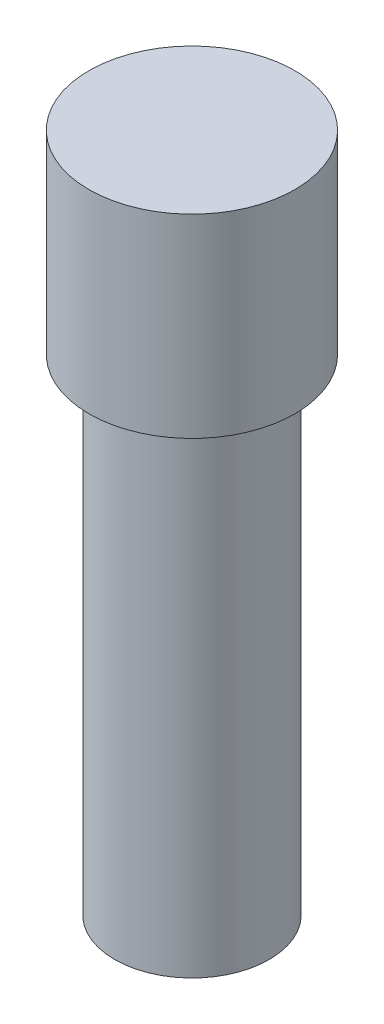
SolidWorks part; units mm, degrees
ref_plane "Alzado" through (0, 0, 0) normal (0, 0, 1) x (1, 0, 0)
ref_plane "Planta" through (0, 0, 0) normal (0, 1, 0) x (1, 0, 0)
ref_plane "Vista lateral" through (0, 0, 0) normal (1, 0, 0) x (0, 0, -1)
sketch "Croquis2" plane through (0, 0, 0) normal (0, 1, 0) x (1, 0, 0)
  circle A0 centre (0, 0) radius 4.775
  dimension "D1" = 9.55
extrude "Saliente-Extruir1" add sketch "Croquis2" along normal blind 30
sketch "Croquis3" plane through (0, 30, 0) normal (0, 1, 0) x (1, 0, 0)
  circle A0 centre (0, 0) radius 6.365
  dimension "D1" = 12.73
extrude "Saliente-Extruir2" add sketch "Croquis3" along normal blind 12
